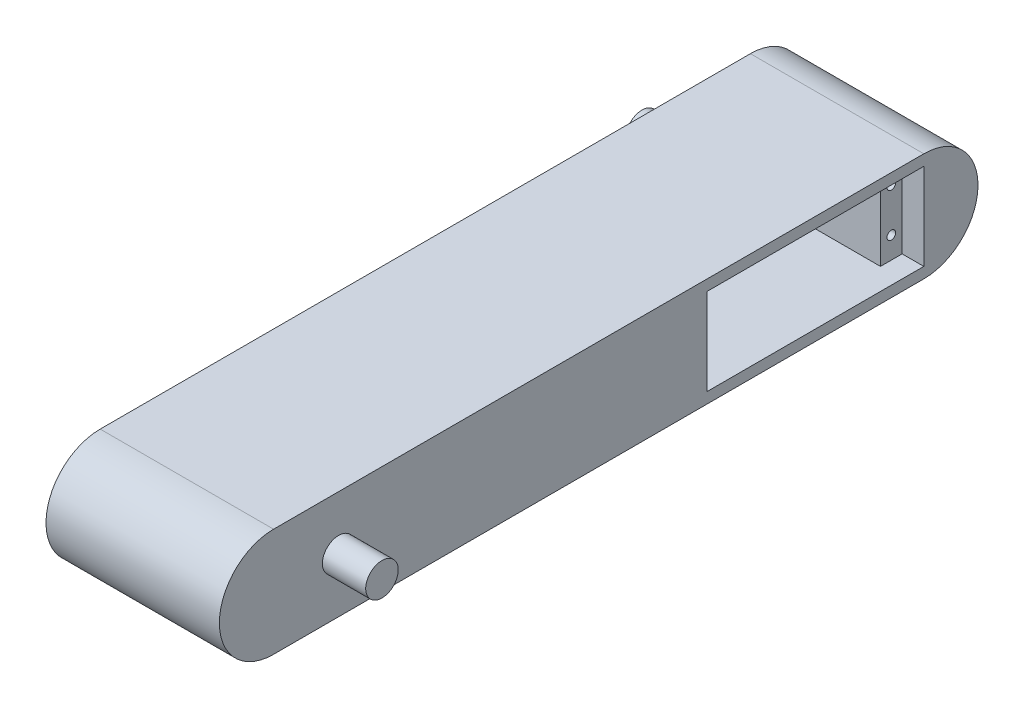
SolidWorks part; units mm, degrees
material "ABS"
ref_plane "Front Plane" through (0, 0, 0) normal (0, 0, 1) x (1, 0, 0)
ref_plane "Top Plane" through (0, 0, 0) normal (0, 1, 0) x (1, 0, 0)
ref_plane "Right Plane" through (0, 0, 0) normal (1, 0, 0) x (0, 0, -1)
sketch "Sketch1" plane through (0, 0, 0) normal (0, 1, 0) x (1, 0, 0)
  line L0 (-17.5, 20) -> (-17.5, 10) construction
  line L1 (-17.5, 20) -> (17.5, 20)
  line L2 (-17.5, 20) -> (-17.5, -20)
  line L3 (-17.5, -20) -> (17.5, -20)
  line L4 (17.5, 20) -> (17.5, -20)
  line L5 (-17.5, 20) -> (17.5, -20) construction
  line L6 (-17.5, -20) -> (17.5, 20) construction
  line L7 (-17.5, 20) -> (-12.5, 20)
  line L8 (-17.5, 20) -> (-17.5, 25)
  line L9 (-17.5, 25) -> (-12.5, 25)
  line L10 (-12.5, 20) -> (-12.5, 25)
  line L11 (-17.5, -20) -> (-12.5, -20)
  line L12 (-17.5, -20) -> (-17.5, -25)
  line L13 (-17.5, -25) -> (-12.5, -25)
  line L14 (-12.5, -20) -> (-12.5, -25)
  line L15 (-12.5, 25) -> (22.5, 25)
  line L16 (22.5, 25) -> (22.5, -25)
  line L17 (22.5, -25) -> (-12.5, -25)
  line L18 (-12.5, -20) -> (17.5, -20)
  line L19 (17.5, 20) -> (-12.5, 20)
  point P0 (0, 0)
  dimension "D1" = 40
  dimension "D2" = 35
  dimension "D3" = 5
  dimension "D4" = 5
  dimension "D5" = 5
  dimension "D6" = 5
  dimension "D7" = 10
  dimension "D8" = 35
extrude "Boss-Extrude1" add sketch "Sketch1" along normal blind 20 contours L17 L16 L15 L10 L1 L4 L3 L14
sketch "Sketch2" plane through (-12.5, 0, 0) normal (-1, 0, 0) x (0, 0, 1)
  line L0 (-25, 10) -> (-20, 10)
  line L2 (-20, 20) -> (-20, 0) construction
  line L3 (-25, 20) -> (-25, 0) construction
  line L4 (-22.5, 15) -> (-22.5, 5)
  point P7 (-22.5, 10)
  point P10 (-22.5, 10)
  dimension "D1" = 10
hole_wizard "Ø2.0mm Dowel Hole1" positions "Sketch6" profile "Sketch7" hole size "Ø2.0" standard "ANSI Metric"
sketch "Sketch6" plane through (-12.5, 0, 0) normal (-1, 0, 0) x (0, 0, 1)
  point P0 (-22.5, 15)
  point P3 (-22.5, 5)
sketch "Sketch7" plane through (-12.5, 15, -22.5) normal (0, 1, 0) x (0, 0, 1)
  line L0 (0, 0) -> (0, 10.6009)
  line L1 (0, 10.6009) -> (1, 10)
  line L2 (1, 10) -> (1, 0)
  line L5 (1, 0) -> (0, 0)
  line L10 (0, 10.6009) -> (-1, 10) construction
  line L11 (0, -6.35) -> (0, 107.95) construction
  dimension "Hole Dia." = 2
  dimension "Hole Depth" = 10
  dimension "Drill Angle" = 118
mirror "Mirror1" about plane through (0, 0, 0) normal (0, 0, 1) of "Ø2.0mm Dowel Hole1"
sketch "Sketch8" plane through (22.5, 0, 0) normal (1, 0, 0) x (0, 0, -1)
  line L0 (-25, 10) -> (-10, 10)
  line L1 (-25, 20) -> (-25, 0) construction
  circle A0 centre (-10, 10) radius 3.75
  dimension "D2" = 7.5
  dimension "D1" = 15
extrude "Boss-Extrude2" add sketch "Sketch8" along normal blind 10
sketch "Sketch9" plane through (0, 20, 0) normal (0, 1, 0) x (1, 0, 0)
  line L1 (22.5, -25) -> (-12.5, -25)
  line L2 (22.5, -25) -> (22.5, 25)
  line L3 (22.5, 25) -> (-12.5, 25)
  line L4 (-12.5, -25) -> (-12.5, 25)
extrude "Boss-Extrude3" add sketch "Sketch9" along normal blind 2.5
sketch "Sketch10" plane through (0, 0, 0) normal (0, -1, 0) x (1, 0, 0)
  line L1 (-12.5, -25) -> (22.5, -25)
  line L2 (-12.5, -25) -> (-12.5, 25)
  line L3 (-12.5, 25) -> (22.5, 25)
  line L4 (22.5, -25) -> (22.5, 25)
extrude "Boss-Extrude4" add sketch "Sketch10" along normal blind 2.5
sketch "Sketch11" plane through (0, 0, -25) normal (0, 0, -1) x (-1, 0, 0)
  line L1 (12.5, 22.5) -> (-22.5, 22.5)
  line L2 (12.5, 22.5) -> (12.5, -2.5)
  line L3 (12.5, -2.5) -> (-22.5, -2.5)
  line L4 (-22.5, 22.5) -> (-22.5, -2.5)
extrude "Boss-Extrude5" add sketch "Sketch11" along normal blind 100
sketch "Sketch12" plane through (-12.5, 0, 0) normal (-1, 0, 0) x (0, 0, 1)
  line L0 (-125, 22.5) -> (25, 22.5)
  line L1 (-25, 20) -> (25, 20)
  line L2 (-25, 20) -> (-25, 0)
  line L3 (-25, 0) -> (25, 0)
  line L4 (25, 20) -> (25, 0)
  line L5 (-25, 20) -> (25, 0) construction
  line L6 (-25, 0) -> (25, 20) construction
  line L7 (25, 22.5) -> (25, 20)
  line L8 (-25, 20) -> (-25, 0)
  line L9 (25, 0) -> (25, -2.5)
  line L10 (25, -2.5) -> (-125, -2.5)
  line L11 (-125, -2.5) -> (-125, 22.5)
  point P0 (0, 10)
  line M4 (-125, -2.5) -> (25, -2.5)
  line M5 (25, -2.5) -> (25, 22.5)
  line M6 (25, 22.5) -> (-125, 22.5)
  line M7 (-125, 22.5) -> (-125, -2.5)
  line M11 (20, 0) -> (-20, 0)
  line M13 (-20, 20) -> (20, 20)
  dimension "D1" = 50
  dimension "D2" = 20
extrude "Boss-Extrude6" add sketch "Sketch12" along normal blind 5 contours L3 L2 L1 M13 M5 M6 M7 M4 M11
sketch "Sketch20" plane through (22.5, 0, 0) normal (1, 0, 0) x (0, 0, -1)
  line L0 (-10, 10) -> (120, 10) construction
  line L1 (125, 22.5) -> (125, -2.5)
  arc A0 (125, 22.5) -> (125, -2.5) centre (125, 10) cw
  dimension "D1" = 130
extrude "Boss-Extrude9" add sketch "Sketch20" against normal blind 40
sketch "Sketch23" plane through (22.5, 0, 0) normal (1, 0, 0) x (0, 0, -1)
  line L0 (-25, -2.5) -> (-25, 22.5)
  arc A0 (-25, 22.5) -> (-25, -2.5) centre (-25, 10) ccw
extrude "Boss-Extrude10" add sketch "Sketch23" against normal blind 40
sketch "Sketch24" plane through (22.5, 0, 0) normal (1, 0, 0) x (0, 0, -1)
  line L0 (-10, 10) -> (110, 10) construction
  line L1 (110, 10) -> (120, 10) construction
  line L2 (120, 10) -> (120, 20) construction
  line L3 (120, 20) -> (125, 20) construction
  line L4 (120, 20) -> (80, 20)
  line L5 (120, 20) -> (120, 0)
  line L6 (120, 0) -> (80, 0)
  line L7 (80, 20) -> (80, 0)
  line L9 (125, 20) -> (75, 20)
  line L10 (125, 20) -> (125, 0)
  line L11 (125, 0) -> (75, 0)
  line L12 (75, 20) -> (75, 0)
  dimension "D1" = 120
  dimension "D2" = 10
  dimension "D3" = 10
  dimension "D4" = 40
  dimension "D5" = 20
  dimension "D6" = 5
  dimension "D7" = 50
  dimension "D8" = 20
extrude "Cut-Extrude4" cut sketch "Sketch24" against normal blind 5 contours L12 L11 L10 L9
sketch "Sketch26" plane through (22.5, 0, 0) normal (1, 0, 0) x (0, 0, -1)
  line L0 (125, 20) -> (120, 20) construction
  line L1 (125, 20) -> (75, 20) construction
  line L2 (125, 0) -> (75, 0) construction
  line L3 (120, 20) -> (80, 20)
  line L4 (120, 20) -> (120, 0)
  line L5 (120, 0) -> (80, 0)
  line L6 (80, 20) -> (80, 0)
  dimension "D1" = 5
  dimension "D2" = 40
extrude "Cut-Extrude5" cut sketch "Sketch26" against normal blind 35
sketch "Sketch27" plane through (17.5, 0, 0) normal (1, 0, 0) x (0, 0, -1)
  line L0 (125, 10) -> (120, 10)
  line L2 (120, 0) -> (120, 20) construction
  line L3 (125, 20) -> (125, 0) construction
  line L4 (122.5, 15) -> (122.5, 5)
  line L5 (75, 10) -> (80, 10)
  line L7 (80, 20) -> (80, 0) construction
  line L8 (75, 20) -> (75, 0) construction
  line L9 (77.5, 15) -> (77.5, 5)
  point P7 (122.5, 10)
  point P10 (122.5, 10)
  point P17 (77.5, 10)
  point P20 (77.5, 10)
  dimension "D1" = 10
  dimension "D2" = 10
hole_wizard "Ø2.0mm Dowel Hole2" positions "Sketch28" profile "Sketch29" hole size "Ø2.0" standard "ANSI Metric"
sketch "Sketch28" plane through (17.5, 0, 0) normal (1, 0, 0) x (0, 0, -1)
  point P0 (77.5, 15)
  point P3 (77.5, 5)
  point P6 (122.5, 15)
  point P9 (122.5, 5)
sketch "Sketch29" plane through (17.5, 15, -77.5) normal (0, 1, 0) x (0, 0, -1)
  line L0 (0, 0) -> (0, 10.6009)
  line L1 (0, 10.6009) -> (1, 10)
  line L2 (1, 10) -> (1, 0)
  line L5 (1, 0) -> (0, 0)
  line L10 (0, 10.6009) -> (-1, 10) construction
  line L11 (0, -6.35) -> (0, 107.95) construction
  dimension "Hole Dia." = 2
  dimension "Hole Depth" = 10
  dimension "Drill Angle" = 118
sketch "Sketch30" plane through (-17.5, 0, 0) normal (-1, 0, 0) x (0, 0, 1)
  line L0 (-125, 10) -> (-110, 10) construction
  circle A0 centre (-110, 10) radius 3.75
  dimension "D2" = 7.5
  dimension "D1" = 15
extrude "Boss-Extrude11" add sketch "Sketch30" along normal blind 10
